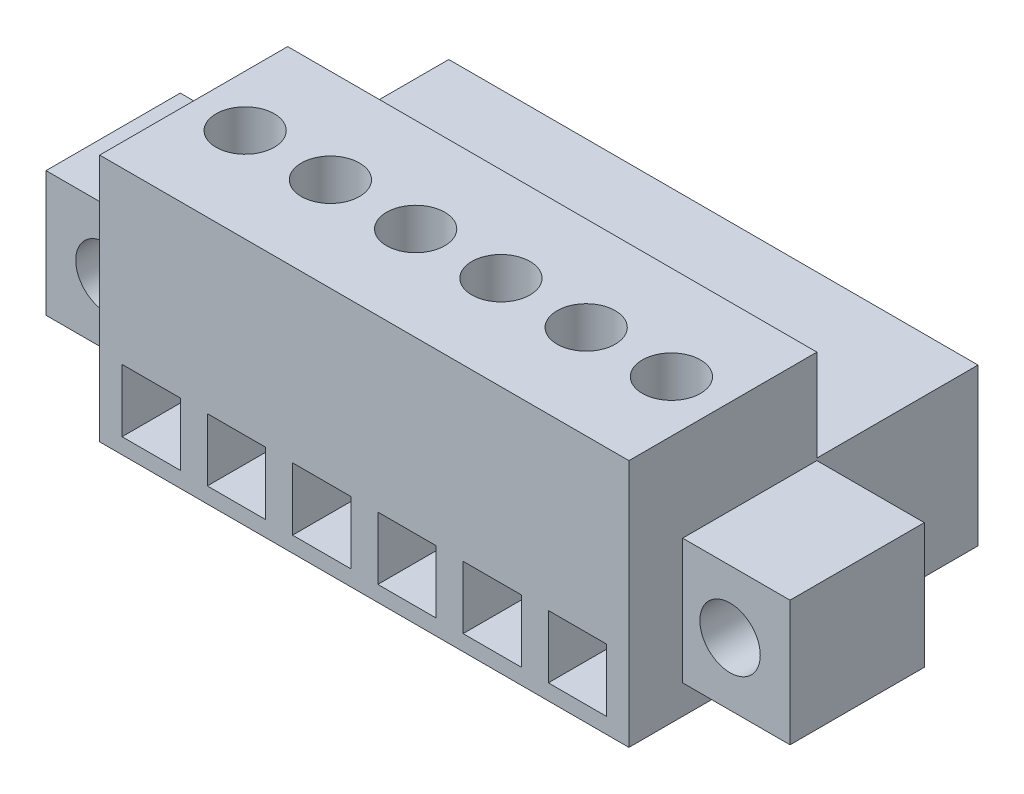
SolidWorks part; units mm, degrees
ref_plane "Front Plane" through (0, 0, 0) normal (0, 0, 1) x (1, 0, 0)
ref_plane "Top Plane" through (0, 0, 0) normal (0, 1, 0) x (1, 0, 0)
ref_plane "Right Plane" through (0, 0, 0) normal (1, 0, 0) x (0, 0, -1)
ref_plane "PL mating face" through (0, 0, 3) normal (0, 0, 1) x (1, 0, 0)
sketch "SK Body" plane through (0, 0, 3) normal (0, 0, 1) x (1, 0, 0)
  line L0 (-11.825, -4.1) -> (11.825, -4.1)
  line L1 (11.825, -4.1) -> (11.825, 7)
  line L2 (11.825, 7) -> (-11.825, 7)
  line L3 (-11.825, 7) -> (-11.825, -4.1)
extrude "Body" add sketch "SK Body" along normal blind 8.4
sketch "SK Flange ears" plane through (0, 0, 3) normal (0, 0, 1) x (1, 0, 0)
  line L0 (11.825, -2.8) -> (16.625, -2.8)
  line L1 (16.625, -2.8) -> (16.625, 2.8)
  line L2 (16.625, 2.8) -> (11.825, 2.8)
  line L3 (11.825, 2.8) -> (11.825, -2.8)
  line L4 (-16.625, -2.8) -> (-11.825, -2.8)
  line L5 (-11.825, -2.8) -> (-11.825, 2.8)
  line L6 (-11.825, 2.8) -> (-16.625, 2.8)
  line L7 (-16.625, 2.8) -> (-16.625, -2.8)
extrude "Flange ears" add sketch "SK Flange ears" along normal blind 6
sketch "SK Nose" plane through (0, 0, 3) normal (0, 0, 1) x (1, 0, 0)
  line L0 (-11.825, -4.1) -> (11.825, -4.1)
  line L1 (11.825, -4.1) -> (11.825, 2.9)
  line L2 (11.825, 2.9) -> (-11.825, 2.9)
  line L3 (-11.825, 2.9) -> (-11.825, -4.1)
extrude "Nose" add sketch "SK Nose" against normal blind 7.2
sketch "SK Flange screw holes" plane through (0, 0, 0) normal (0, 0, 1) x (1, 0, 0)
  circle A0 centre (-13.945, 0) radius 1.35
  circle A1 centre (13.945, 0) radius 1.35
extrude "Flange screw holes" cut sketch "SK Flange screw holes" against normal through all and the other way through all
ref_plane "PL wire face" through (0, 0, 11.4) normal (0, 0, 1) x (1, 0, 0)
sketch "SK Wire entries" plane through (0, 0, 11.4) normal (0, 0, 1) x (1, 0, 0)
  line L0 (-10.825, -3.4) -> (-8.225, -3.4)
  line L1 (-8.225, -3.4) -> (-8.225, -0.6)
  line L2 (-8.225, -0.6) -> (-10.825, -0.6)
  line L3 (-10.825, -0.6) -> (-10.825, -3.4)
  line L4 (-7.015, -3.4) -> (-4.415, -3.4)
  line L5 (-4.415, -3.4) -> (-4.415, -0.6)
  line L6 (-4.415, -0.6) -> (-7.015, -0.6)
  line L7 (-7.015, -0.6) -> (-7.015, -3.4)
  line L8 (-3.205, -3.4) -> (-0.605, -3.4)
  line L9 (-0.605, -3.4) -> (-0.605, -0.6)
  line L10 (-0.605, -0.6) -> (-3.205, -0.6)
  line L11 (-3.205, -0.6) -> (-3.205, -3.4)
  line L12 (0.605, -3.4) -> (3.205, -3.4)
  line L13 (3.205, -3.4) -> (3.205, -0.6)
  line L14 (3.205, -0.6) -> (0.605, -0.6)
  line L15 (0.605, -0.6) -> (0.605, -3.4)
  line L16 (4.415, -3.4) -> (7.015, -3.4)
  line L17 (7.015, -3.4) -> (7.015, -0.6)
  line L18 (7.015, -0.6) -> (4.415, -0.6)
  line L19 (4.415, -0.6) -> (4.415, -3.4)
  line L20 (8.225, -3.4) -> (10.825, -3.4)
  line L21 (10.825, -3.4) -> (10.825, -0.6)
  line L22 (10.825, -0.6) -> (8.225, -0.6)
  line L23 (8.225, -0.6) -> (8.225, -3.4)
extrude "Wire entries" cut sketch "SK Wire entries" against normal blind 6
ref_plane "PL nose tip" through (0, 0, -4.2) normal (0, 0, 1) x (1, 0, 0)
sketch "SK Contact openings" plane through (0, 0, -4.2) normal (0, 0, 1) x (1, 0, 0)
  line L0 (-10.325, -1.4) -> (-8.725, -1.4)
  line L1 (-8.725, -1.4) -> (-8.725, 0.2)
  line L2 (-8.725, 0.2) -> (-10.325, 0.2)
  line L3 (-10.325, 0.2) -> (-10.325, -1.4)
  line L4 (-6.515, -1.4) -> (-4.915, -1.4)
  line L5 (-4.915, -1.4) -> (-4.915, 0.2)
  line L6 (-4.915, 0.2) -> (-6.515, 0.2)
  line L7 (-6.515, 0.2) -> (-6.515, -1.4)
  line L8 (-2.705, -1.4) -> (-1.105, -1.4)
  line L9 (-1.105, -1.4) -> (-1.105, 0.2)
  line L10 (-1.105, 0.2) -> (-2.705, 0.2)
  line L11 (-2.705, 0.2) -> (-2.705, -1.4)
  line L12 (1.105, -1.4) -> (2.705, -1.4)
  line L13 (2.705, -1.4) -> (2.705, 0.2)
  line L14 (2.705, 0.2) -> (1.105, 0.2)
  line L15 (1.105, 0.2) -> (1.105, -1.4)
  line L16 (4.915, -1.4) -> (6.515, -1.4)
  line L17 (6.515, -1.4) -> (6.515, 0.2)
  line L18 (6.515, 0.2) -> (4.915, 0.2)
  line L19 (4.915, 0.2) -> (4.915, -1.4)
  line L20 (8.725, -1.4) -> (10.325, -1.4)
  line L21 (10.325, -1.4) -> (10.325, 0.2)
  line L22 (10.325, 0.2) -> (8.725, 0.2)
  line L23 (8.725, 0.2) -> (8.725, -1.4)
extrude "Contact openings" cut sketch "SK Contact openings" along normal blind 6.2
ref_plane "PL top face" through (0, 7, 0) normal (0, 1, 0) x (1, 0, 0)
sketch "SK Clamp screw holes" plane through (0, 7, 0) normal (0, 1, 0) x (1, 0, 0)
  circle A0 centre (-9.525, -7.2) radius 1.3
  circle A1 centre (-5.715, -7.2) radius 1.3
  circle A2 centre (-1.905, -7.2) radius 1.3
  circle A3 centre (1.905, -7.2) radius 1.3
  circle A4 centre (5.715, -7.2) radius 1.3
  circle A5 centre (9.525, -7.2) radius 1.3
extrude "Clamp screw holes" cut sketch "SK Clamp screw holes" against normal blind 3
